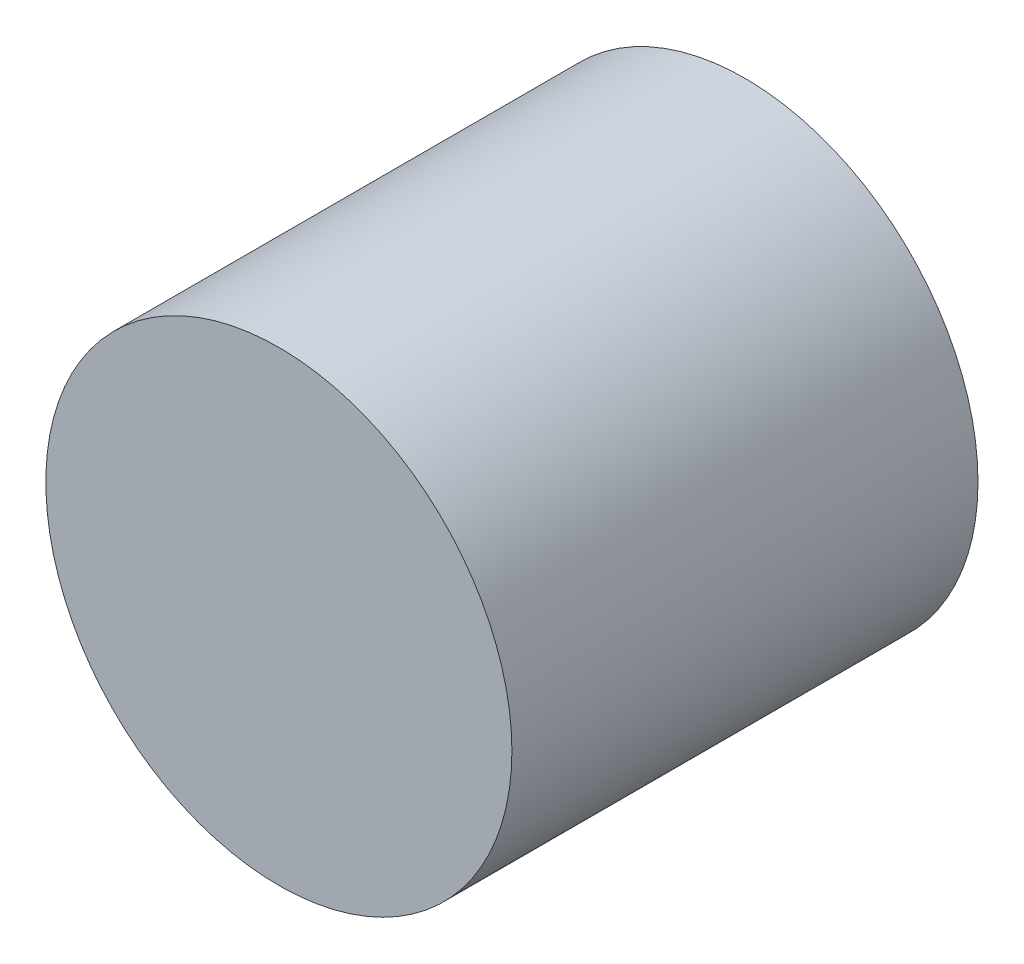
SolidWorks part; units mm, degrees
ref_plane "Front Plane" through (0, 0, 0) normal (0, 0, 1) x (1, 0, 0)
ref_plane "Top Plane" through (0, 0, 0) normal (0, 1, 0) x (1, 0, 0)
ref_plane "Right Plane" through (0, 0, 0) normal (1, 0, 0) x (0, 0, -1)
sketch "Sketch1" plane through (0, 0, 0) normal (0, 0, 1) x (1, 0, 0)
  circle A0 centre (0, 0) radius 1.5
extrude "Boss-Extrude1" add sketch "Sketch1" against normal blind 3
